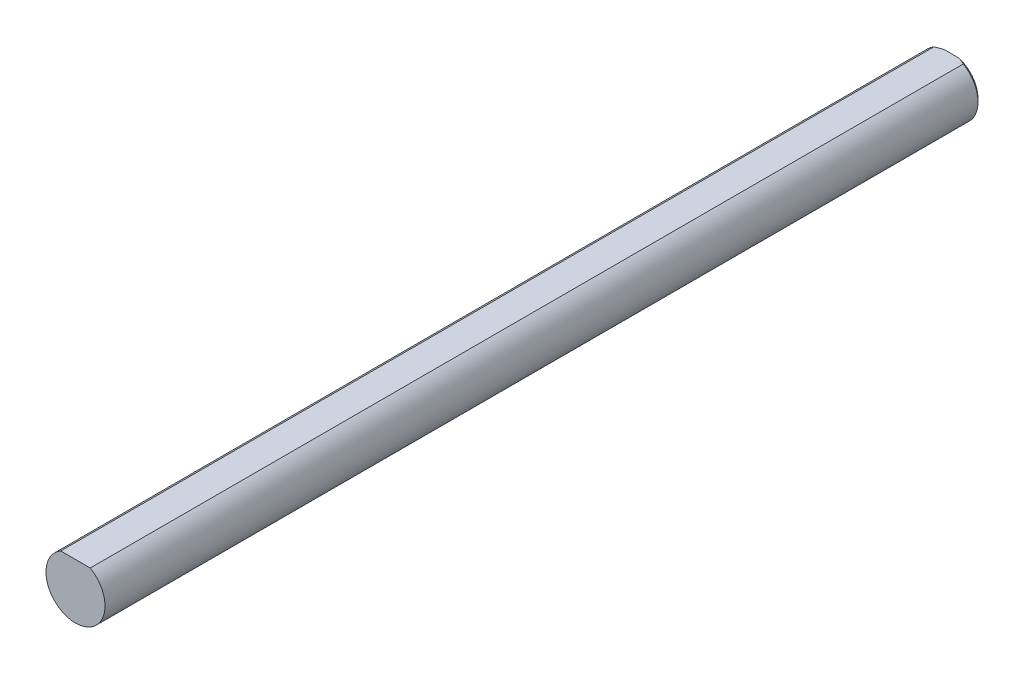
SolidWorks part; units mm, degrees
ref_plane "Front Plane" through (0, 0, 0) normal (0, 0, 1) x (1, 0, 0)
ref_plane "Top Plane" through (0, 0, 0) normal (0, 1, 0) x (1, 0, 0)
ref_plane "Right Plane" through (0, 0, 0) normal (1, 0, 0) x (0, 0, -1)
sketch "Sketch1" plane through (0, 0, 0) normal (0, 0, 1) x (1, 0, 0)
  line L0 (-1.5875, 2.7496) -> (1.5875, 2.7496) construction
  circle A1 centre (0, 0) radius 3.175 construction
  dimension "Diameter" = 6.35
  dimension "Flat Width" = 3.175
sketch "Sketch2" plane through (0, 0, 0) normal (1, 0, 0) x (0, 0, -1)
  line L0 (-76.2, 3.175) -> (76.2, 3.175) construction
  line L1 (0, 3.175) -> (0, -3.175) construction
  line L2 (0, 3.175) -> (0, -3.175) construction
  line L3 (-76.2, 3.175) -> (-76.2, -3.175) construction
  line L4 (-76.2, -3.175) -> (76.2, -3.175) construction
  point P2 (0, 3.175)
  point P3 (63.5, 3.175)
  point P4 (-63.5, 3.175)
  dimension "Length" = 152.4
  dimension "D2" = 12.7
  dimension "D1" = 12.7
  dimension "D-Profile Length" = 152.4
sketch "Sketch3" plane through (0, 0, 0) normal (0, 0, 1) x (1, 0, 0)
  circle A1 centre (0, 0) radius 3.175 construction
  circle A3 centre (0, 0) radius 3.175
extrude "Boss-Extrude2" add sketch "Sketch3" along normal up to vertex (76.2 mm away) and the other way up to vertex (76.2 mm away) up to point (0, 3.175, 76.2) other way up to point (0, 3.175, -76.2)
sketch "Sketch10" plane through (0, 0, 0) normal (0, 0, 1) x (1, 0, 0)
  line L0 (-1.5875, 2.7496) -> (1.5875, 2.7496)
  line L1 (0, 0) -> (0, 3.175) construction
  circle A0 centre (0, 0) radius 3.175 construction
  circle A1 centre (0, 0) radius 3.175 construction
  arc A2 (-1.5875, 2.7496) -> (1.5875, 2.7496) centre (0, 0) cw
extrude "Cut-Extrude5" cut sketch "Sketch10" against normal through all both and the other way through all
chamfer "Chamfer1" distance 0.3175 angle 45 4 edges at (0, -3.175, 76.2) (0, -3.175, -76.2) (0, 2.7496, -76.2) (0, 2.7496, 76.2)
sketch "Sketch11" plane through (0, 0, 76.2) normal (0, 0, 1) x (1, 0, 0)
  line L1 (-4.7889, -4.1028) -> (4.7889, -4.1028)
  line L2 (-4.7889, -4.1028) -> (-4.7889, 4.1028)
  line L3 (-4.7889, 4.1028) -> (4.7889, 4.1028)
  line L4 (4.7889, -4.1028) -> (4.7889, 4.1028)
  line L5 (-4.7889, -4.1028) -> (4.7889, 4.1028) construction
  line L6 (-4.7889, 4.1028) -> (4.7889, -4.1028) construction
  point P0 (0, 0)
extrude "Cut-Extrude6" cut sketch "Sketch11" against normal blind 58.2
equation "\"D1@Chamfer1\"= \"Diameter@Sketch1\" / 20"
equation "\"D1@Sketch2\"=\"Diameter@Sketch1\"*2"
equation "\"D2@Sketch2\"=\"D1@Sketch2\""
